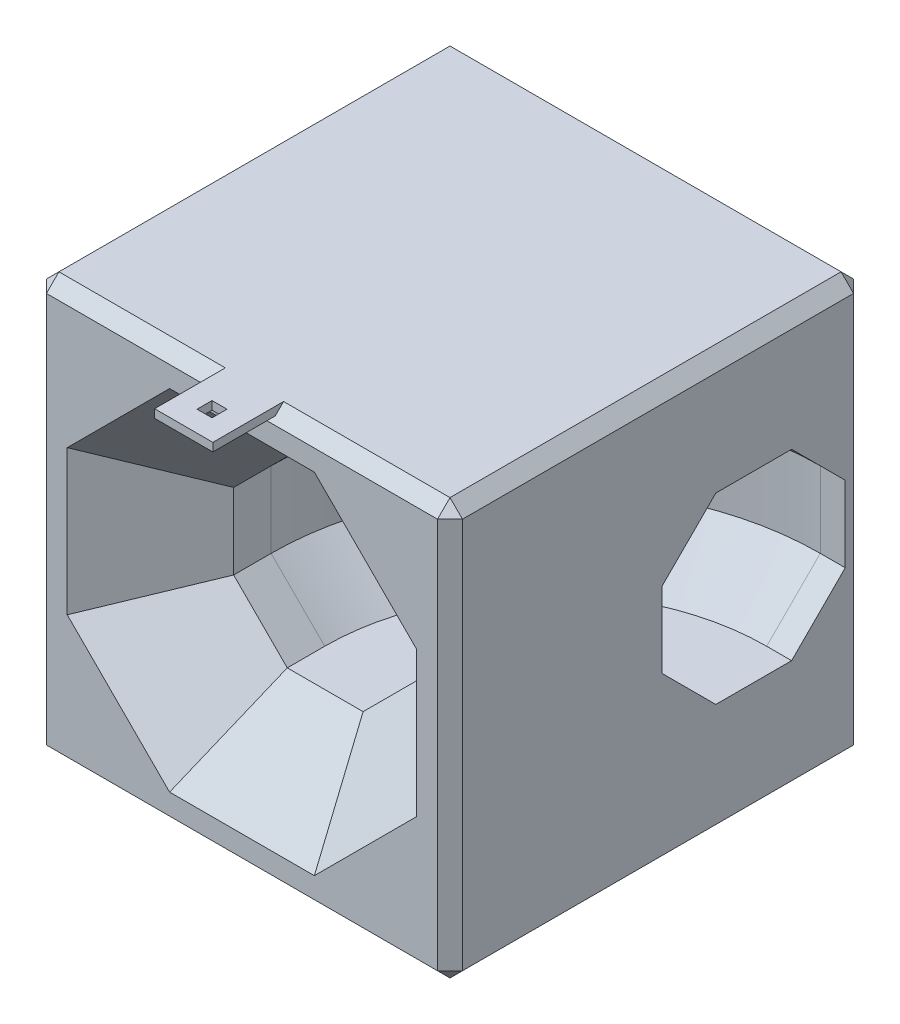
SolidWorks part; units mm, degrees
ref_plane "Front" through (0, 0, 0) normal (0, 0, 1) x (1, 0, 0)
ref_plane "Top" through (0, 0, 0) normal (0, 1, 0) x (1, 0, 0)
ref_plane "Right" through (0, 0, 0) normal (1, 0, 0) x (0, 0, -1)
sketch "Sketch1" plane through (0, 0, 0) normal (0, 0, 1) x (1, 0, 0)
  line L1 (0, 0) -> (50, 0)
  line L2 (0, 0) -> (0, 50)
  line L3 (0, 50) -> (50, 50)
  line L4 (50, 0) -> (50, 50)
  dimension "D1" = 50
extrude "Boss-Extrude1" add sketch "Sketch1" along normal blind 50
ref_plane "Plane1" through (0, 25, 0) normal (0, -1, 0) x (-1, 0, 0)
sketch "Sketch8" plane through (50, 0, 0) normal (1, 0, 0) x (0, 0, -1)
  line L0 (-25, 0) -> (-25, 25) construction
  line L1 (-2.5, 14) -> (-24.5, 14) construction
  line L2 (-2.5, 14) -> (-2.5, 36) construction
  line L3 (-2.5, 36) -> (-24.5, 36) construction
  line L4 (-24.5, 14) -> (-24.5, 36) construction
  line L5 (-2.5, 14) -> (-24.5, 36) construction
  line L6 (-2.5, 36) -> (-24.5, 14) construction
  line L8 (-50, 0) -> (0, 0) construction
  line L10 (-25, 25) -> (-13.5, 25) construction
  line L11 (-2.5, 29.5563) -> (-8.9437, 36)
  line L12 (-8.9437, 36) -> (-18.0563, 36)
  line L13 (-18.0563, 36) -> (-24.5, 29.5563)
  line L14 (-24.5, 29.5563) -> (-24.5, 20.4437)
  line L15 (-24.5, 20.4437) -> (-18.0563, 14)
  line L16 (-18.0563, 14) -> (-8.9437, 14)
  line L17 (-8.9437, 14) -> (-2.5, 20.4437)
  line L18 (-2.5, 20.4437) -> (-2.5, 29.5563)
  line L19 (-13.5, 25) -> (0, 25) construction
  line L20 (0, 0) -> (0, 50) construction
  circle A0 centre (-13.5, 25) radius 11 construction
  point P0 (-13.5, 25)
  dimension "D1" = 22
  dimension "D2" = 2.5
sketch "Sketch9" plane through (0, 25, 0) normal (0, -1, 0) x (-1, 0, 0)
  line L0 (-50, -13.5) -> (-47, -13.5)
  line L1 (-25, -35.5) -> (-25, -50)
  line L2 (-50, -50) -> (0, -50) construction
  arc A0 (-47, -13.5) -> (-25, -35.5) centre (-47, -35.5) cw
  dimension "D2" = 3
sweep "Cut-Sweep5" cut profiles "Sketch8" path "Sketch9"
chamfer "Chamfer1" distance 10 angle 45 8 edges at (36, 25, 50) (32.7782, 32.7782, 50) (25, 36, 50) (17.2218, 32.7782, 50) (14, 25, 50) (17.2218, 17.2218, 50) (25, 14, 50) (32.7782, 17.2218, 50)
chamfer "Chamfer2" distance 1.5 angle 45 12 edges at (25, 50, 0) (0, 25, 0) (0, 50, 25) (25, 50, 50) (0, 25, 50) (0, 0, 25) (25, 0, 0) (50, 25, 0) (50, 50, 25) (25, 0, 50) (50, 0, 25) (50, 25, 50)
sketch "Sketch10" plane through (0, 0, 50) normal (0, 0, 1) x (1, 0, 0)
  line L0 (1.5, 50) -> (48.5, 50) construction
  line L1 (21.5, 50) -> (28.5, 50)
  line L2 (21.5, 50) -> (21.5, 49)
  line L3 (21.5, 49) -> (28.5, 49)
  line L4 (28.5, 50) -> (28.5, 49)
  point P6 (25, 50)
  dimension "D1" = 7
  dimension "D2" = 1
extrude "Boss-Extrude2" add sketch "Sketch10" along normal blind 7 and the other way blind 10
sketch "Sketch11" plane through (0, 49, 0) normal (0, -1, 0) x (1, 0, 0)
  line L0 (25, 54.5) -> (25, 57) construction
  line L1 (24.1, 54.5) -> (25.9, 54.5)
  line L2 (24.1, 54.5) -> (24.1, 52.7)
  line L3 (24.1, 52.7) -> (25.9, 52.7)
  line L4 (25.9, 54.5) -> (25.9, 52.7)
  line L5 (21.5, 57) -> (28.5, 57) construction
  dimension "D1" = 2.5
  dimension "D2" = 1.8
extrude "Cut-Extrude1" cut sketch "Sketch11" against normal blind 7
